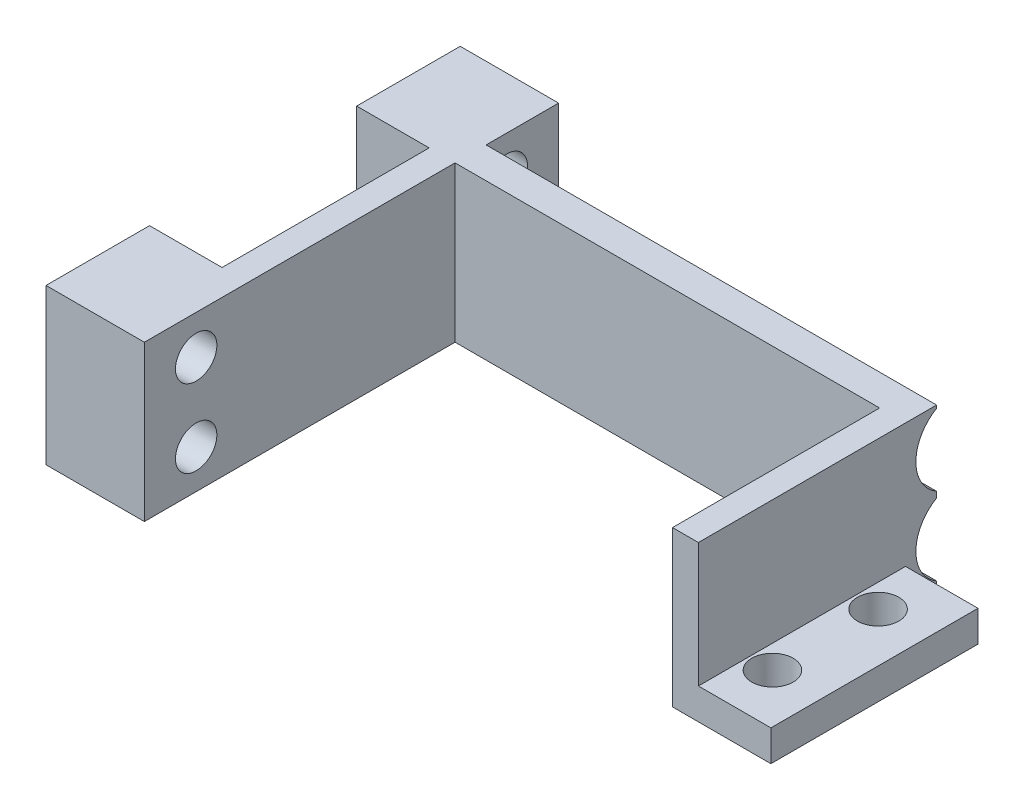
SolidWorks part; units mm, degrees
ref_plane "Front Plane" through (0, 0, 0) normal (0, 0, 1) x (1, 0, 0)
ref_plane "Top Plane" through (0, 0, 0) normal (0, 1, 0) x (1, 0, 0)
ref_plane "Right Plane" through (0, 0, 0) normal (1, 0, 0) x (0, 0, -1)
sketch "Sketch1" plane through (0, 0, 0) normal (0, 0, 1) x (1, 0, 0)
  line L1 (0, 0) -> (46, 0)
  line L2 (0, 0) -> (0, 15)
  line L3 (0, 15) -> (46, 15)
  line L4 (46, 0) -> (46, 15)
  dimension "D1" = 46
  dimension "D2" = 15
extrude "Boss-Extrude1" add sketch "Sketch1" along normal blind 3
sketch "Sketch3" plane through (0, 0, 3) normal (0, 0, 1) x (1, 0, 0)
  line L1 (0, 0) -> (2.5, 0)
  line L2 (0, 0) -> (0, 15)
  line L3 (0, 15) -> (2.5, 15)
  line L4 (2.5, 0) -> (2.5, 15)
  dimension "D1" = 15
  dimension "D2" = 2.5
extrude "Boss-Extrude2" add sketch "Sketch3" along normal blind 20
sketch "Sketch4" plane through (0, 0, 0) normal (-1, 0, 0) x (0, 0, 1)
  line L1 (23, 15) -> (3, 15)
  line L2 (23, 15) -> (23, 12)
  line L3 (23, 12) -> (3, 12)
  line L4 (3, 15) -> (3, 12)
  dimension "D1" = 3
  dimension "D2" = 20
extrude "Boss-Extrude3" add sketch "Sketch4" along normal blind 7
sketch "Sketch5" plane through (0, 15, 0) normal (0, 1, 0) x (1, 0, 0)
  line L0 (0, -3) -> (0, -23) construction
  line L1 (-2.25, -23) -> (-2.25, -20.35) construction
  line L2 (2.5, -23) -> (-7, -23) construction
  line L3 (-2.25, -23) -> (0, -23) construction
  line L4 (-7, -13) -> (2.5, -13) construction
  line L5 (-7, -23) -> (-7, -3) construction
  line L6 (2.5, -23) -> (2.5, -3) construction
  circle A0 centre (-2.25, -18.1) radius 2.25 construction
  circle A1 centre (-2.25, -18.1) radius 2
  circle A2 centre (-2.25, -7.9) radius 2
  dimension "D2" = 4.5
  dimension "D4" = 4
  dimension "D1" = 2.65
  dimension "D3" = 2.25
extrude "Cut-Extrude1" cut sketch "Sketch5" against normal blind 7
ref_plane "Plane1" through (23, 0, 0) normal (1, 0, 0) x (0, 0, -1)
mirror "Mirror1" about plane through (23, 0, 0) normal (1, 0, 0) of "Boss-Extrude2", "Boss-Extrude3", "Cut-Extrude1"
ref_plane "Plane2" through (-7, 12, 23) normal (0, 1, 0) x (1, 0, 0)
ref_plane "Plane3" through (0, 0, 13) normal (0, 0, 1) x (1, 0, 0)
sketch "Sketch7" plane through (0, 0, 23) normal (0, 0, 1) x (1, 0, 0)
  line L1 (2.5, 15) -> (-7, 15)
  line L2 (2.5, 15) -> (2.5, 0)
  line L3 (2.5, 0) -> (-7, 0)
  line L4 (-7, 15) -> (-7, 0)
  dimension "D1" = 9.5
extrude "Boss-Extrude4" add sketch "Sketch7" along normal blind 10
sketch "Sketch8" plane through (-7, 0, 0) normal (-1, 0, 0) x (0, 0, 1)
  line L0 (28, 0) -> (28, 15) construction
  line L1 (33, 0) -> (23, 0) construction
  line L2 (33, 15) -> (3, 15) construction
  line L3 (33, 7.5) -> (23, 7.5) construction
  line L4 (33, 15) -> (33, 0) construction
  line L5 (23, 12) -> (23, 0) construction
  circle A0 centre (28, 11.25) radius 2
  circle A1 centre (28, 3.75) radius 2
  dimension "D1" = 4
  dimension "D2" = 3.75
extrude "Cut-Extrude2" cut sketch "Sketch8" against normal blind 10
mirror "Mirror4" about plane through (0, 0, 13) normal (0, 0, 1) of "Cut-Extrude2", "Boss-Extrude4"
ref_plane "Plane4" through (0, -10, 0) normal (0, 1, 0) x (1, 0, 0)
mirror "Mirror6" about plane through (0, -10, 0) normal (0, 1, 0) of bodies 111
delete or keep bodies "Body-Delete/Keep 1" type delete bodies bodies 111
sketch "Sketch10" plane through (2.5, 0, 0) normal (1, 0, 0) x (0, 0, -1)
  arc A0 (3.3919, -27.5) -> (0.6081, -27.5) centre (2, -23.75) ccw
  arc A1 (0.6081, -27.5) -> (3.3919, -27.5) centre (2, -31.25) ccw
  dimension "D1" = 8
  dimension "D2" = 8
extrude "Cut-Extrude3" cut sketch "Sketch10" along normal up to next
